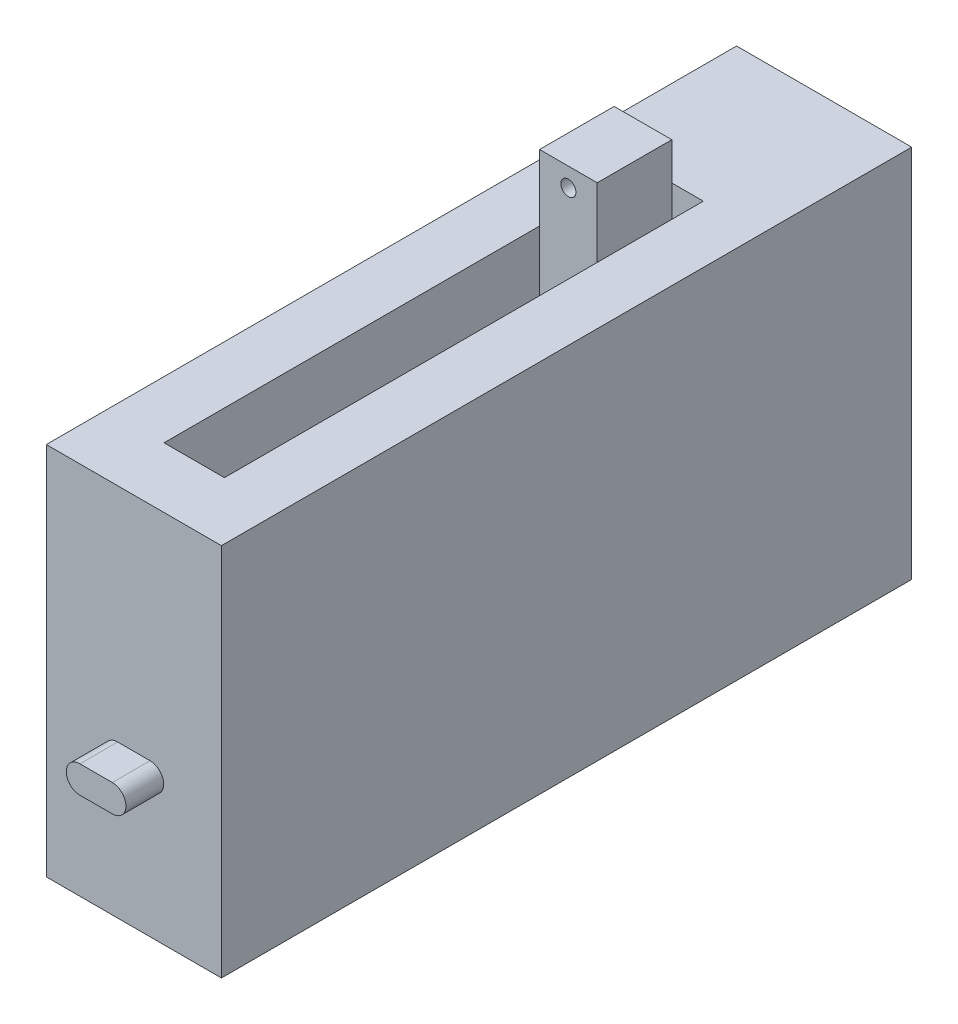
SolidWorks part; units mm, degrees
ref_plane "Front Plane" through (0, 0, 0) normal (0, 0, 1) x (1, 0, 0)
ref_plane "Top Plane" through (0, 0, 0) normal (0, 1, 0) x (1, 0, 0)
ref_plane "Right Plane" through (0, 0, 0) normal (1, 0, 0) x (0, 0, -1)
sketch "Sketch1" plane through (0, 0, 0) normal (0, 1, 0) x (1, 0, 0)
  line L1 (-3.683, -14.5161) -> (3.683, -14.5161)
  line L2 (-3.683, -14.5161) -> (-3.683, 14.5161)
  line L3 (-3.683, 14.5161) -> (3.683, 14.5161)
  line L4 (3.683, -14.5161) -> (3.683, 14.5161)
  line L5 (-3.683, -14.5161) -> (3.683, 14.5161) construction
  line L6 (-3.683, 14.5161) -> (3.683, -14.5161) construction
  point P0 (0, 0)
  dimension "D1" = 7.366
  dimension "D2" = 29.0322
extrude "Boss-Extrude1" add sketch "Sketch1" along normal blind 15.748
sketch "Sketch2" plane through (0, 15.748, 0) normal (0, 1, 0) x (1, 0, 0)
  line L0 (0, -1.905) -> (0, 0) construction
  line L1 (-1.27, -11.9761) -> (1.27, -11.9761)
  line L2 (-1.27, -11.9761) -> (-1.27, 8.1661)
  line L3 (-1.27, 8.1661) -> (1.27, 8.1661)
  line L4 (1.27, -11.9761) -> (1.27, 8.1661)
  line L5 (-1.27, -11.9761) -> (1.27, 8.1661) construction
  line L6 (-1.27, 8.1661) -> (1.27, -11.9761) construction
  line L7 (3.683, 14.5161) -> (-3.683, 14.5161) construction
  line L8 (-3.683, -14.5161) -> (3.683, -14.5161) construction
  point P0 (0, -1.905)
  dimension "D1" = 6.35
  dimension "D2" = 2.54
  dimension "D3" = 2.54
extrude "Cut-Extrude1" cut sketch "Sketch2" against normal blind 3.175
sketch "Sketch3" plane through (0, 12.573, 0) normal (0, 1, 0) x (1, 0, 0)
  line L0 (0, 5.3277) -> (0, 0) construction
  line L1 (1.2129, 6.8961) -> (-1.2128, 6.8961)
  line L2 (1.2129, 6.8961) -> (1.2129, 3.7592)
  line L3 (1.2129, 3.7592) -> (-1.2129, 3.7592)
  line L4 (-1.2128, 6.8961) -> (-1.2129, 3.7592)
  line L5 (1.2129, 6.8961) -> (-1.2129, 3.7592) construction
  line L6 (1.2129, 3.7592) -> (-1.2128, 6.8961) construction
  line L8 (1.27, 8.1661) -> (-1.27, 8.1661) construction
  point P0 (0, 5.3277)
  dimension "D1" = 2.4257
  dimension "D2" = 3.1369
  dimension "D3" = 1.27
extrude "Boss-Extrude2" add sketch "Sketch3" along normal offset from surface (6.0198 mm away) 2.8448 up to face at (0, 15.748, 1.905) offset beyond the face yes
sketch "Sketch4" plane through (0, 0, -6.8961) normal (0, 0, -1) x (-1, 0, 0)
  line L0 (1.2128, 18.5928) -> (-1.2129, 18.5928) construction
  circle A0 centre (0, 17.7991) radius 0.3175
  dimension "D2" = 0.635
  dimension "D1" = 0.7937
extrude "Cut-Extrude2" cut sketch "Sketch4" against normal through all
sketch "Sketch5" plane through (0, 0, 14.5161) normal (0, 0, 1) x (1, 0, 0)
  line L1 (-0.6827, 5.842) -> (0.6827, 5.842) construction
  line L2 (-0.6827, 6.414) -> (0.6827, 6.414)
  line L3 (-0.6827, 5.27) -> (0.6827, 5.27)
  line L4 (-3.683, 0) -> (3.683, 0) construction
  arc A1 (-0.6827, 6.414) -> (-0.6827, 5.27) centre (-0.6827, 5.842) ccw
  arc A2 (0.6827, 5.27) -> (0.6827, 6.414) centre (0.6827, 5.842) ccw
  point P6 (0, 5.842)
  dimension "D1" = 5.842
extrude "Boss-Extrude3" add sketch "Sketch5" along normal blind 1.5875
